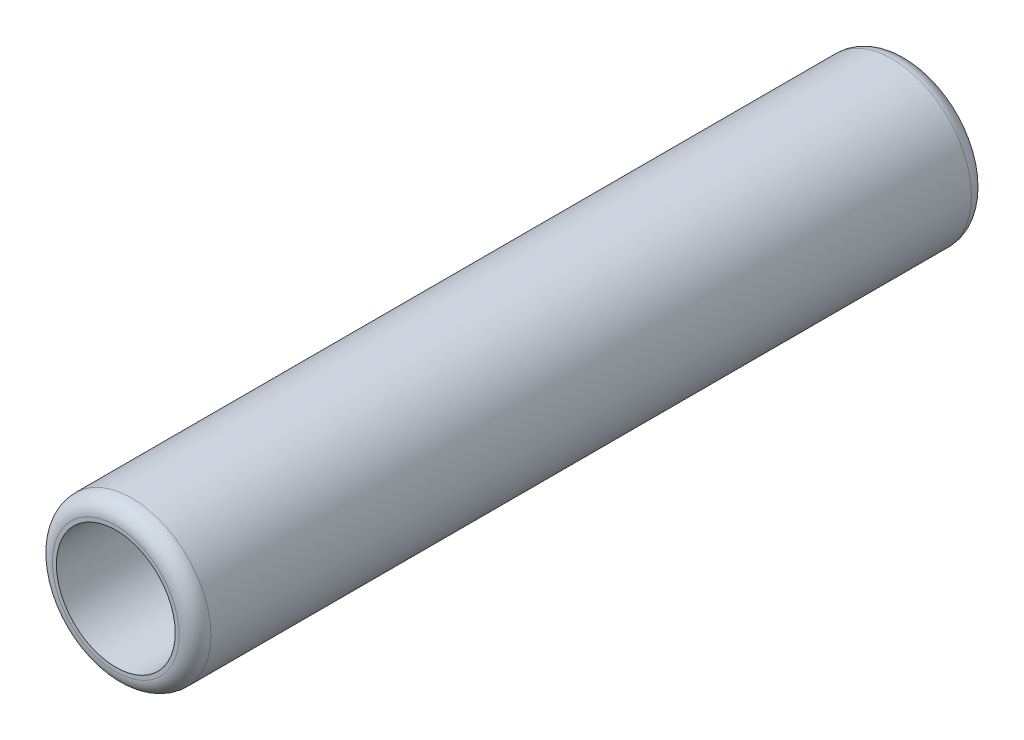
SolidWorks part; units mm, degrees
ref_plane "Front Plane" through (0, 0, 0) normal (0, 0, 1) x (1, 0, 0)
ref_plane "Top Plane" through (0, 0, 0) normal (0, 1, 0) x (1, 0, 0)
ref_plane "Right Plane" through (0, 0, 0) normal (1, 0, 0) x (0, 0, -1)
sketch "Sketch1" plane through (0, 0, 0) normal (0, 0, 1) x (1, 0, 0)
  circle A0 centre (0, 0) radius 10
  circle A1 centre (0, 0) radius 7.5
  dimension "D1" = 20
  dimension "D2" = 15
extrude "Boss-Extrude1" add sketch "Sketch1" along normal blind 100
fillet "Fillet2" radius 2 2 edges at (10, 0, 0) (10, 0, 100)
